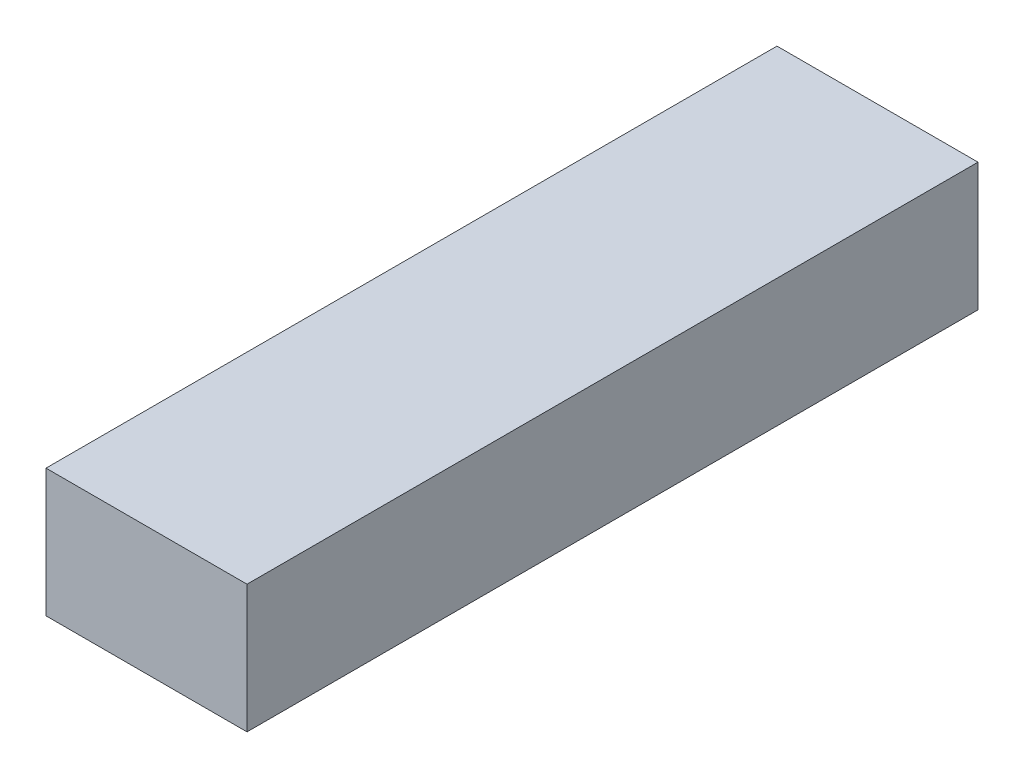
SolidWorks part; units mm, degrees
material "1.0553 (S355J0)"
ref_plane "Front Plane" through (0, 0, 0) normal (0, 0, 1) x (1, 0, 0)
ref_plane "Top Plane" through (0, 0, 0) normal (0, 1, 0) x (1, 0, 0)
ref_plane "Right Plane" through (0, 0, 0) normal (1, 0, 0) x (0, 0, -1)
sketch "Sketch1" plane through (0, 0, 0) normal (0, 0, 1) x (1, 0, 0)
  line L1 (-11, -7) -> (11, -7)
  line L2 (-11, -7) -> (-11, 7)
  line L3 (-11, 7) -> (11, 7)
  line L4 (11, -7) -> (11, 7)
  line L5 (-11, -7) -> (11, 7) construction
  line L6 (-11, 7) -> (11, -7) construction
  point P0 (0, 0)
  dimension "D1" = 22
  dimension "D2" = 14
extrude "Boss-Extrude1" add sketch "Sketch1" against normal blind 80
